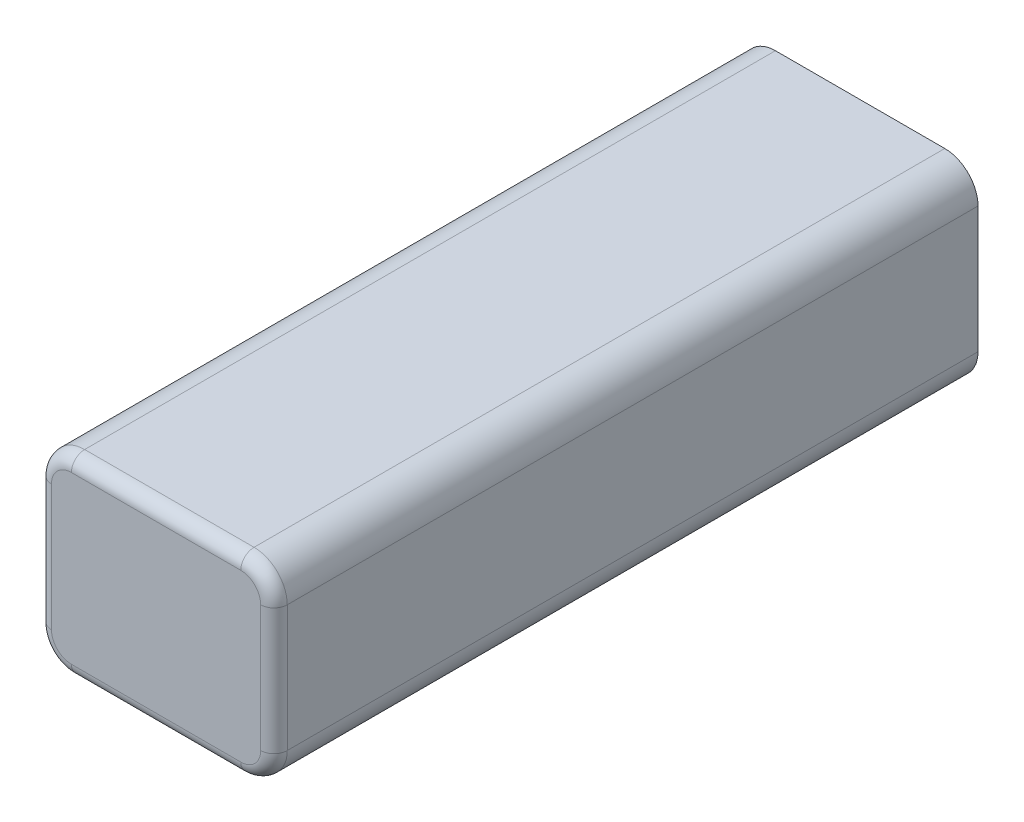
SolidWorks part; units mm, degrees
ref_plane "前视基准面" through (0, 0, 0) normal (0, 0, 1) x (1, 0, 0)
ref_plane "上视基准面" through (0, 0, 0) normal (0, 1, 0) x (1, 0, 0)
ref_plane "右视基准面" through (0, 0, 0) normal (1, 0, 0) x (0, 0, -1)
sketch "草图1" plane through (0, 0, 0) normal (0, 0, 1) x (1, 0, 0)
  line L1 (-17.75, 14.5) -> (17.75, 14.5)
  line L2 (-17.75, 14.5) -> (-17.75, -14.5)
  line L3 (-17.75, -14.5) -> (17.75, -14.5)
  line L4 (17.75, 14.5) -> (17.75, -14.5)
  line L5 (-17.75, 14.5) -> (17.75, -14.5) construction
  line L6 (-17.75, -14.5) -> (17.75, 14.5) construction
  point P0 (0, 0)
  dimension "D1" = 35.5
  dimension "D2" = 29
extrude "凸台-拉伸1" add sketch "草图1" along normal blind 106
fillet "圆角1" radius 5 4 edges at (17.75, -14.5, 53) (-17.75, -14.5, 53) (-17.75, 14.5, 53) (17.75, 14.5, 53)
fillet "圆角2" radius 2 8 edges at (-16.2855, -13.0355, 106) (-17.75, 0, 106) (-16.2855, 13.0355, 106) (0, 14.5, 106) (16.2855, 13.0355, 106) (17.75, 0, 106) (16.2855, -13.0355, 106) (0, -14.5, 106)
